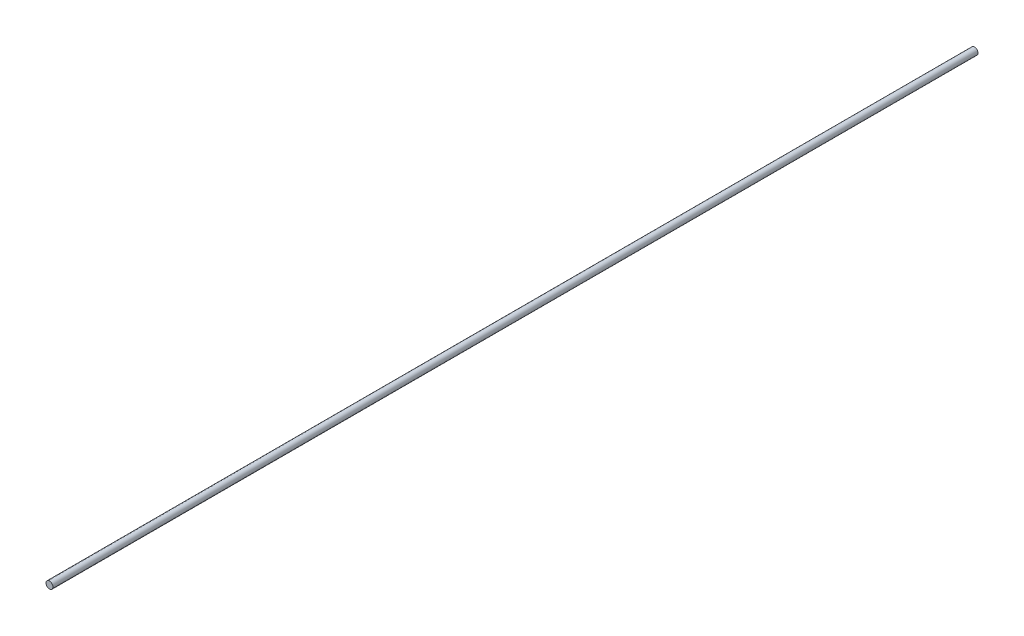
SolidWorks part; units mm, degrees
material "Hexcel AS4C (3000 Filaments)"
ref_plane "Front Plane" through (0, 0, 0) normal (0, 0, 1) x (1, 0, 0)
ref_plane "Top Plane" through (0, 0, 0) normal (0, 1, 0) x (1, 0, 0)
ref_plane "Right Plane" through (0, 0, 0) normal (1, 0, 0) x (0, 0, -1)
sketch "Sketch1" plane through (0, 0, 0) normal (0, 0, 1) x (1, 0, 0)
  circle A0 centre (0, 0) radius 1.5
  dimension "D1" = 3
extrude "Boss-Extrude1" add sketch "Sketch1" along normal blind 400
